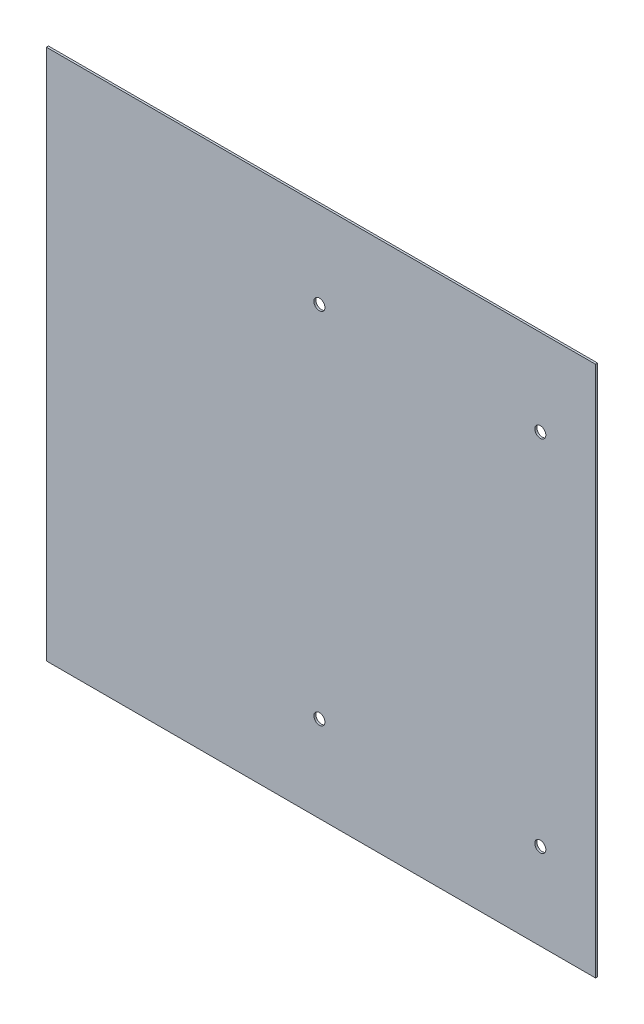
SolidWorks part; units mm, degrees
ref_plane "Front Plane" through (0, 0, 0) normal (0, 0, 1) x (1, 0, 0)
ref_plane "Top Plane" through (0, 0, 0) normal (0, 1, 0) x (1, 0, 0)
ref_plane "Right Plane" through (0, 0, 0) normal (1, 0, 0) x (0, 0, -1)
sketch "Sketch1" plane through (0, 0, 0) normal (0, 0, 1) x (1, 0, 0)
  line L1 (231.0713, 0) -> (628.8, 0)
  line L2 (231.0713, 0) -> (231.0713, -385)
  line L3 (231.0713, -385) -> (628.8, -385)
  line L4 (628.8, 0) -> (628.8, -385)
extrude "Boss-Extrude1" add sketch "Sketch1" along normal blind 1.5
sketch "Sketch2" plane through (0, 0, 1.5) normal (0, 0, 1) x (1, 0, 0)
  line L0 (231.0713, -192.5) -> (628.8, -192.5) construction
  line L1 (231.0713, 0) -> (231.0713, -385) construction
  line L2 (628.8, -385) -> (628.8, 0) construction
  line L3 (429.9357, 0) -> (429.9357, -385) construction
  line L4 (628.8, 0) -> (231.0713, 0) construction
  line L5 (231.0713, -385) -> (628.8, -385) construction
  line L6 (508.8, -192.5) -> (508.8, -222.7716) construction
  line L7 (428.8, -62.5) -> (588.8, -62.5) construction
  line L8 (428.8, -62.5) -> (428.8, -322.5) construction
  line L9 (428.8, -322.5) -> (588.8, -322.5) construction
  line L10 (588.8, -62.5) -> (588.8, -322.5) construction
  line L11 (428.8, -62.5) -> (588.8, -322.5) construction
  line L12 (428.8, -322.5) -> (588.8, -62.5) construction
  circle A0 centre (588.8, -62.5) radius 4
  circle A1 centre (588.8, -322.5) radius 4
  circle A2 centre (428.8, -62.5) radius 4
  circle A3 centre (428.8, -322.5) radius 4
  point P14 (508.8, -192.5)
  dimension "D3" = 8
  dimension "D1" = 260
  dimension "D2" = 160
  dimension "D4" = 40
extrude "Cut-Extrude1" cut sketch "Sketch2" against normal blind 1.5
